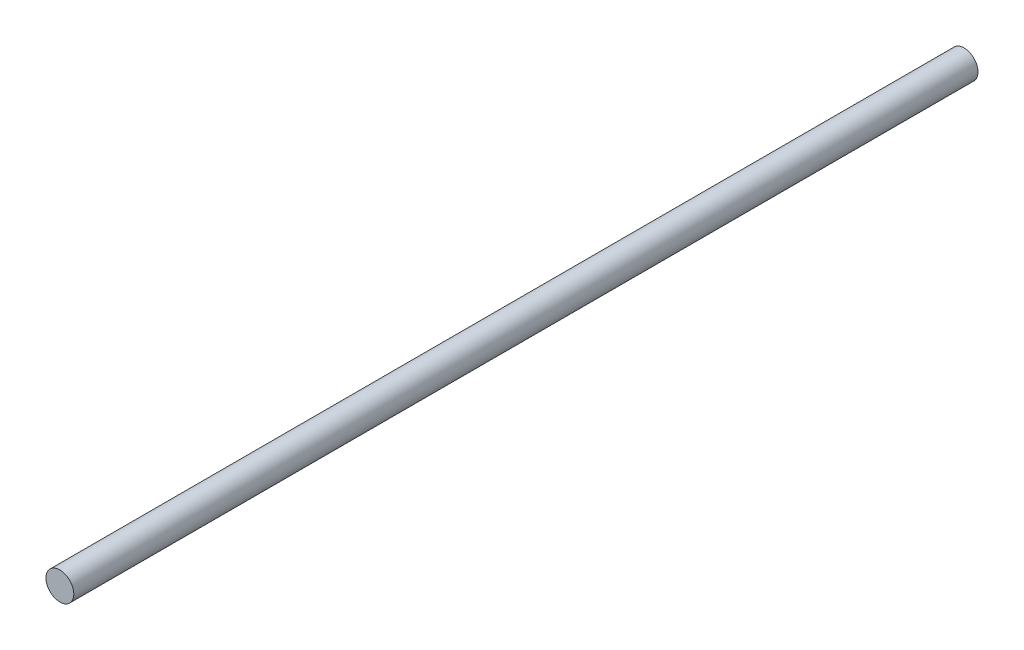
SolidWorks part; units mm, degrees
ref_plane "Front Plane" through (0, 0, 0) normal (0, 0, 1) x (1, 0, 0)
ref_plane "Top Plane" through (0, 0, 0) normal (0, 1, 0) x (1, 0, 0)
ref_plane "Right Plane" through (0, 0, 0) normal (1, 0, 0) x (0, 0, -1)
sketch "Sketch1" plane through (0, 0, 0) normal (0, 0, 1) x (1, 0, 0)
  circle A0 centre (0, 0) radius 4
  dimension "D1" = 8
extrude "Boss-Extrude1" add sketch "Sketch1" along normal blind 260
